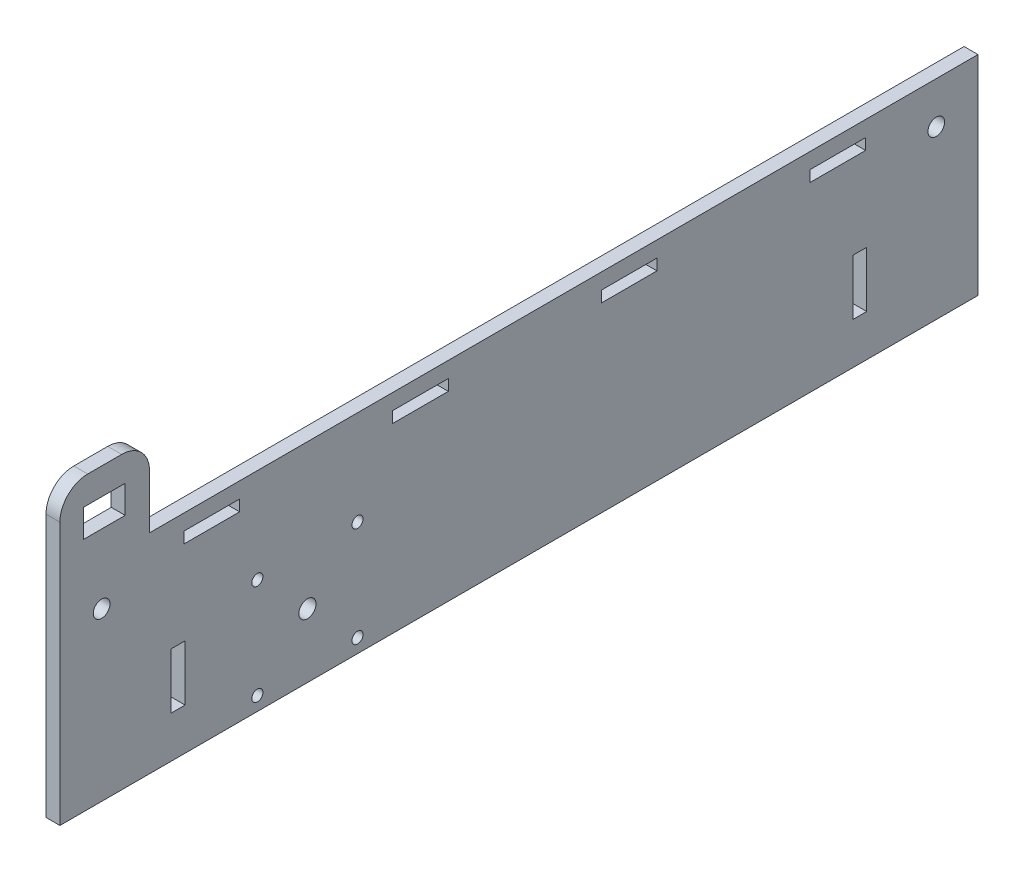
SolidWorks part; units mm, degrees
other "Markup1"
sketch "Sketch4" plane through (5, 30, 10) normal (0.9006, 0.1104, 0.4203) x (0.4243, -0.0149, -0.9054)
ref_plane "Front Plane" through (0, 0, 0) normal (0, 0, 1) x (1, 0, 0)
ref_plane "Top Plane" through (0, 0, 0) normal (0, 1, 0) x (1, 0, 0)
ref_plane "Right Plane" through (0, 0, 0) normal (1, 0, 0) x (0, 0, -1)
sketch "Sketch5" plane through (0, 0, 0) normal (1, 0, 0) x (0, 0, -1)
  line L0 (79.6063, 44.3441) -> (99.6063, 44.3441)
  line L1 (-40, -10) -> (0, -10)
  line L2 (-40, -10) -> (-40, 50)
  line L3 (-7.7972, 50) -> (290, 50)
  line L4 (290, -10) -> (290, 50)
  line L5 (4.6063, 44.3441) -> (24.6063, 44.3441)
  line L6 (4.6063, 44.3441) -> (4.6063, 40.3441)
  line L7 (4.6063, 40.3441) -> (24.6063, 40.3441)
  line L8 (24.6063, 44.3441) -> (24.6063, 40.3441)
  line L10 (-40, 50) -> (-40, 69.4281)
  line L11 (-30, 79.4281) -> (-17.7972, 79.4281)
  line L12 (-7.7972, 50) -> (-7.7972, 69.4281)
  line L13 (99.6063, 44.3441) -> (99.6063, 40.3441)
  line L14 (-31.5472, 69.8168) -> (-16.5472, 69.8168)
  line L15 (-31.5472, 69.8168) -> (-31.5472, 59.8168)
  line L16 (-31.5472, 59.8168) -> (-16.5472, 59.8168)
  line L17 (-16.5472, 69.8168) -> (-16.5472, 59.8168)
  line L18 (79.6063, 40.3441) -> (99.6063, 40.3441)
  line L19 (79.6063, 44.3441) -> (79.6063, 40.3441)
  line L20 (154.6063, 44.3441) -> (174.6063, 44.3441)
  line L21 (174.6063, 44.3441) -> (174.6063, 40.3441)
  line L22 (154.6063, 40.3441) -> (174.6063, 40.3441)
  line L23 (154.6063, 44.3441) -> (154.6063, 40.3441)
  line L24 (229.6063, 44.3441) -> (249.6063, 44.3441)
  line L25 (249.6063, 44.3441) -> (249.6063, 40.3441)
  line L26 (229.6063, 40.3441) -> (249.6063, 40.3441)
  line L27 (229.6063, 44.3441) -> (229.6063, 40.3441)
  line L28 (125, -10) -> (125, 125.6475) construction
  line L30 (0, 0) -> (0, 10)
  line L31 (0, 10) -> (5, 10)
  line L32 (5, 0) -> (5, 10)
  line L33 (245, 0) -> (245, 10)
  line L34 (250, 10) -> (245, 10)
  line L35 (250, 0) -> (250, 10)
  line L37 (0, 0) -> (0, -10)
  line L39 (5, -10) -> (5, 0)
  line L40 (5, -10) -> (245, -10)
  line L42 (245, 0) -> (245, -10)
  line L44 (250, 0) -> (250, -10)
  line L45 (250, -10) -> (290, -10)
  circle A0 centre (-25, 35) radius 3
  circle A1 centre (275, 35) radius 3
  arc A3 (-30, 79.4281) -> (-40, 69.4281) centre (-30, 69.4281) ccw
  arc A4 (-7.7972, 69.4281) -> (-17.7972, 79.4281) centre (-17.7972, 69.4281) ccw
  dimension "D1" = 6
  dimension "D2" = 6
  dimension "D10" = 10
  dimension "D9" = 10
  dimension "D3" = 300
  dimension "D4" = 60
  dimension "D5" = 15
  dimension "D6" = 15
  dimension "D7" = 15
  dimension "D8" = 20
  dimension "D12" = 5
  dimension "D13" = 10
  dimension "D14" = 10
  dimension "D15" = 40
  dimension "D16" = 23.75
  dimension "D17" = 60
  dimension "D18" = 19.4281
  dimension "D19" = 4
  dimension "D20" = 330
  dimension "D21" = 10
  dimension "D22" = 15
  dimension "D11" = 4
extrude "Boss-Extrude1" add sketch "Sketch5" along normal blind 5
sketch "Sketch6" plane through (5, 0, 0) normal (1, 0, 0) x (0, 0, -1)
  line L1 (-40, -10) -> (290, -10)
  line L2 (-40, -10) -> (-40, -25)
  line L3 (-40, -25) -> (290, -25)
  line L4 (290, -10) -> (290, -25)
  dimension "D1" = 15
extrude "Boss-Extrude2" add sketch "Sketch6" against normal blind 5
sketch "Sketch8" plane through (5, 0, 0) normal (1, 0, 0) x (0, 0, -1)
  line L0 (-40, -25) -> (290, -25) construction
  line L1 (48.9686, 27.8258) -> (48.9686, -37.9063) construction
  line L2 (30.9686, 16) -> (66.9686, -20) construction
  line L3 (30.9686, -20) -> (66.9686, 16) construction
  circle A1 centre (30.9686, 16) radius 2
  circle A2 centre (30.9686, -20) radius 2
  circle A3 centre (66.9686, -20) radius 2
  circle A4 centre (66.9686, 16) radius 2
  circle A5 centre (48.9686, -2) radius 3.1
  dimension "D1" = 4
  dimension "D2" = 4
  dimension "D6" = 6.2
  dimension "D3" = 36
  dimension "D4" = 5
  dimension "D5" = 18
extrude "Cut-Extrude1" cut sketch "Sketch8" against normal blind 5
